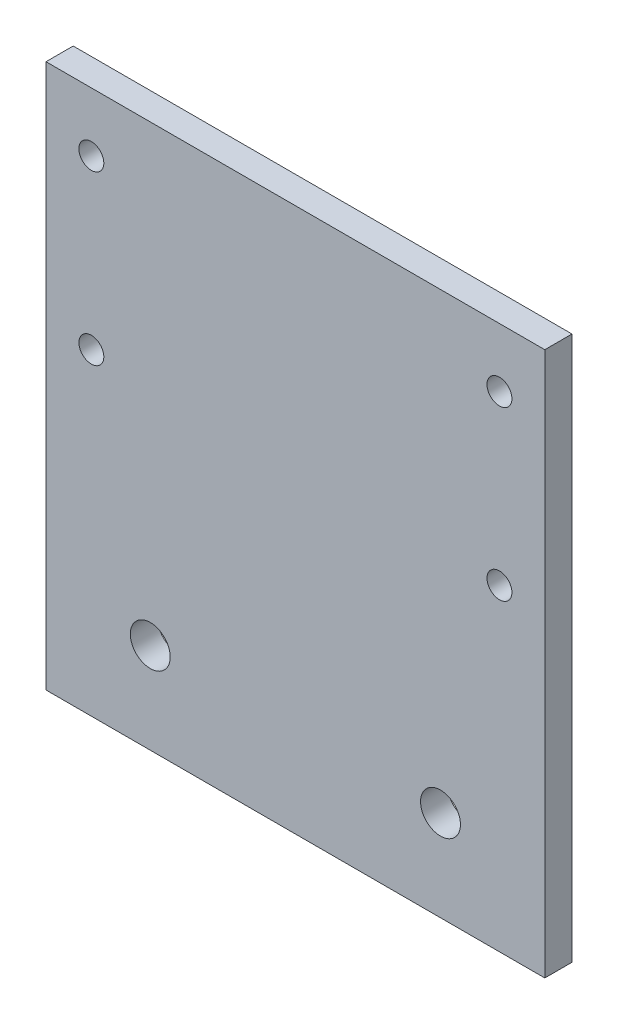
SolidWorks part; units mm, degrees
ref_plane "Front Plane" through (0, 0, 0) normal (0, 0, 1) x (1, 0, 0)
ref_plane "Top Plane" through (0, 0, 0) normal (0, 1, 0) x (1, 0, 0)
ref_plane "Right Plane" through (0, 0, 0) normal (1, 0, 0) x (0, 0, -1)
sketch "Sketch1" plane through (0, 0, 0) normal (0, 0, 1) x (1, 0, 0)
  line L0 (27.5, 60) -> (27.5, 0) construction
  line L1 (0, 0) -> (55, 0)
  line L2 (0, 0) -> (0, 60)
  line L3 (0, 60) -> (55, 60)
  line L4 (55, 0) -> (55, 60)
  line L5 (5, 53.5) -> (50, 53.5) construction
  line L6 (5, 53.5) -> (5, 35) construction
  line L7 (5, 35) -> (50, 35) construction
  line L8 (50, 53.5) -> (50, 35) construction
  line L9 (11.5, 10) -> (43.5, 10) construction
  circle A0 centre (5, 53.5) radius 1.375
  circle A1 centre (50, 53.5) radius 1.375
  circle A2 centre (50, 35) radius 1.375
  circle A3 centre (5, 35) radius 1.375
  circle A4 centre (11.5, 10) radius 2.2
  circle A5 centre (43.5, 10) radius 2.2
  point P11 (27.5, 53.5)
  point P23 (27.5, 10)
  point P24 (0, 0)
  dimension "D6" = 2.75
  dimension "D9" = 4.4
  dimension "D10" = 4.4
  dimension "D1" = 55
  dimension "D2" = 60
  dimension "D3" = 45
  dimension "D4" = 18.5
  dimension "D5" = 35
  dimension "D11" = 32
  dimension "D12" = 20
  dimension "D7" = 2
  dimension "D8" = 2
extrude "Boss-Extrude1" add sketch "Sketch1" along normal blind 3
